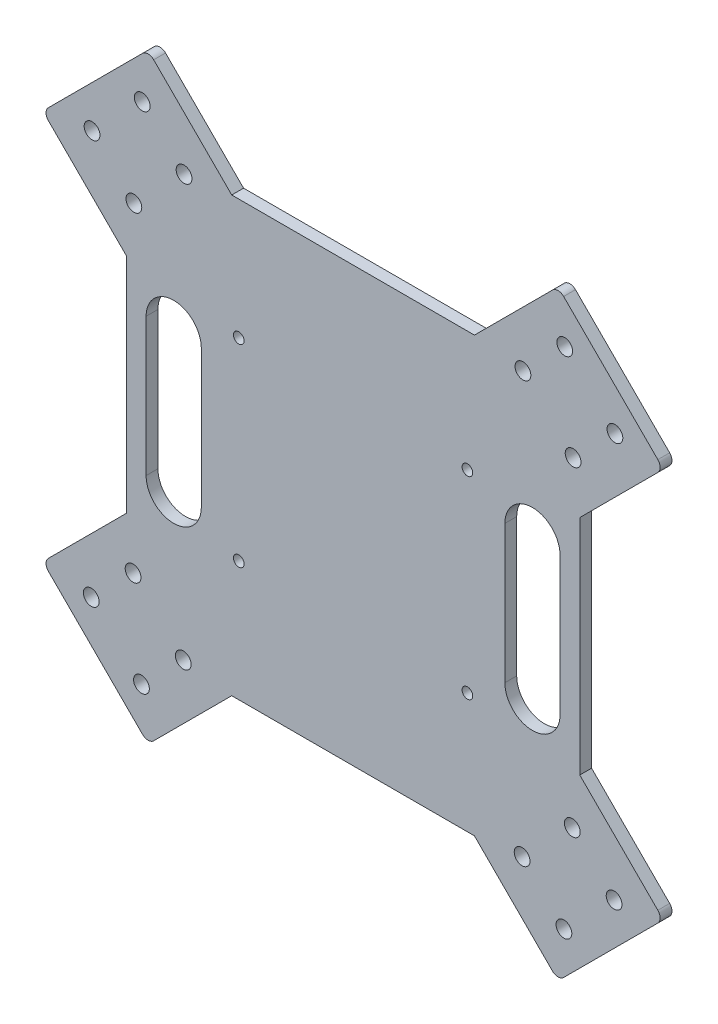
SolidWorks part; units mm, degrees
ref_plane "Front Plane" through (0, 0, 0) normal (0, 0, 1) x (1, 0, 0)
ref_plane "Top Plane" through (0, 0, 0) normal (0, 1, 0) x (1, 0, 0)
ref_plane "Right Plane" through (0, 0, 0) normal (1, 0, 0) x (0, 0, -1)
sketch "Sketch1" plane through (0, 0, 0) normal (0, 0, 1) x (1, 0, 0)
  line L0 (0, 0) -> (0, 47150.9256) construction
  line L1 (0, 0) -> (47150.9256, 0) construction
  line L7 (57.5, -28.28) -> (78.7132, -49.4932)
  line L9 (-30.78, 55) -> (30.78, 55)
  line L10 (-57.5, 28.28) -> (-57.5, -28.28)
  line L11 (-30.78, -55) -> (30.78, -55)
  line L12 (57.5, 28.28) -> (57.5, -28.28)
  line L13 (-57.5, 55) -> (57.5, -55) construction
  line L14 (-57.5, -55) -> (57.5, 55) construction
  line L18 (-29, 24.5) -> (29, 24.5) construction
  line L19 (-29, 24.5) -> (-29, -24.5) construction
  line L20 (-29, -24.5) -> (29, -24.5) construction
  line L21 (29, 24.5) -> (29, -24.5) construction
  line L22 (-29, 24.5) -> (29, -24.5) construction
  line L23 (-29, -24.5) -> (29, 24.5) construction
  line L24 (78.7132, -49.4932) -> (51.9932, -76.2132)
  line L25 (51.9932, -76.2132) -> (30.78, -55)
  line L26 (-57.5, -28.28) -> (-78.7132, -49.4932)
  line L27 (-78.7132, -49.4932) -> (-51.9932, -76.2132)
  line L28 (-51.9932, -76.2132) -> (-30.78, -55)
  line L29 (-51.9932, 76.2132) -> (-30.78, 55)
  line L30 (-78.7132, 49.4932) -> (-51.9932, 76.2132)
  line L31 (-57.5, 28.28) -> (-78.7132, 49.4932)
  line L32 (30.78, 55) -> (51.9932, 76.2132)
  line L33 (51.9932, 76.2132) -> (78.7132, 49.4932)
  line L34 (78.7132, 49.4932) -> (57.5, 28.28)
  line L35 (-28.28, -57.5) -> (-49.4932, -78.7132) [skipped]
  line L36 (-49.4932, -78.7132) -> (-76.2132, -51.9932) [skipped]
  line L37 (-76.2132, -51.9932) -> (-55, -30.78) [skipped]
  line L38 (49.4932, 78.7132) -> (76.2132, 51.9932) [skipped]
  line L39 (76.2132, 51.9932) -> (55, 30.78) [skipped]
  line L40 (28.28, 57.5) -> (49.4932, 78.7132) [skipped]
  circle A4 centre (-29, 24.5) radius 1.35
  circle A5 centre (-29, -24.5) radius 1.35
  circle A6 centre (29, 24.5) radius 1.35
  circle A7 centre (29, -24.5) radius 1.35
  arc A8 (-41.3866, 65.6066) -> (41.3866, 65.6066) centre (0, 141.0479) ccw
  arc A9 (-68.1066, 38.8866) -> (-68.1066, -38.8866) centre (-134.0876, 0) cw
  arc A10 (68.1066, 38.8866) -> (68.1066, -38.8866) centre (134.0876, 0) ccw
  arc A11 (-41.3866, -65.6066) -> (41.3866, -65.6066) centre (0, -141.0479) cw
  point P5 (0, 0)
  point P43 (0, 0)
  dimension "D3" = 58
  dimension "D4" = 2.7
  dimension "D7" = 2.7
  dimension "D8" = 2.7
  dimension "D9" = 2.7
  dimension "D1" = 49
  dimension "D5" = 115
  dimension "D6" = 110
  dimension "D10" = 45
  dimension "D11" = 30
  dimension "D12" = 45
  dimension "D14" = 45
  dimension "D15" = 45
  dimension "D16" = 30
  dimension "D17" = 45
  dimension "D18" = 45
  dimension "D19" = 30
  dimension "D20" = 37.7878
  dimension "D13" = 4
extrude "Boss-Extrude1" add sketch "Sketch1" along normal blind 3 contours L34 L33 L32 L9 L29 L30 L31 L10 L26 L27 L28 L11 L25 L24 L7 L12 A7 A6 A5 A4
sketch "Sketch2" plane through (0, 0, 3) normal (0, 0, 1) x (1, 0, 0)
  line L0 (30.78, 55) -> (57.5, 28.28) construction
  line L1 (44.14, 41.64) -> (71.2882, 68.7882) construction
  line L2 (43.0793, 53.3073) -> (53.6859, 63.9139) construction
  line L3 (43.0793, 53.3073) -> (55.8073, 40.5793) construction
  line L4 (55.8073, 40.5793) -> (66.4139, 51.1859) construction
  line L5 (53.6859, 63.9139) -> (66.4139, 51.1859) construction
  line L6 (43.0793, 53.3073) -> (66.4139, 51.1859) construction
  line L7 (55.8073, 40.5793) -> (53.6859, 63.9139) construction
  line L8 (0, 0) -> (-36037.9104, 34659.328) construction
  line L9 (-57.5, -28.28) -> (-30.78, -55) construction
  line L10 (-78.7132, -49.4932) -> (-51.9932, -76.2132) construction
  line L11 (-65.3532, -62.8532) -> (-37.2147, -34.7147) construction
  line L12 (-78.7132, 49.4932) -> (-51.9932, 76.2132) construction
  line L13 (-57.5, 28.28) -> (-30.78, 55) construction
  line L14 (-66.4139, -51.1859) -> (-55.8073, -40.5793) construction
  line L15 (-66.4139, -51.1859) -> (-53.6859, -63.9139) construction
  line L16 (-53.6859, -63.9139) -> (-43.0793, -53.3073) construction
  line L17 (-55.8073, -40.5793) -> (-43.0793, -53.3073) construction
  line L18 (-66.4139, -51.1859) -> (-43.0793, -53.3073) construction
  line L19 (-53.6859, -63.9139) -> (-55.8073, -40.5793) construction
  line L20 (30.78, -55) -> (57.5, -28.28) construction
  line L21 (-41.3866, 65.6066) -> (-68.1066, 38.8866) construction
  line L22 (-66.207, 51.3928) -> (-53.4791, 64.1207) construction
  line L23 (-66.207, 51.3928) -> (-55.6004, 40.7862) construction
  line L24 (-55.6004, 40.7862) -> (-42.8725, 53.5141) construction
  line L25 (-53.4791, 64.1207) -> (-42.8725, 53.5141) construction
  line L26 (-66.207, 51.3928) -> (-42.8725, 53.5141) construction
  line L27 (-55.6004, 40.7862) -> (-53.4791, 64.1207) construction
  line L28 (-51.9932, 76.2132) -> (-30.78, 55) construction
  line L29 (-57.5, 28.28) -> (-78.7132, 49.4932) construction
  line L31 (42.8725, -53.5141) -> (55.6004, -40.7862) construction
  line L32 (42.8725, -53.5141) -> (53.4791, -64.1207) construction
  line L33 (53.4791, -64.1207) -> (66.207, -51.3928) construction
  line L34 (55.6004, -40.7862) -> (66.207, -51.3928) construction
  line L35 (42.8725, -53.5141) -> (66.207, -51.3928) construction
  line L36 (53.4791, -64.1207) -> (55.6004, -40.7862) construction
  line L55 (-45.5, 17.5) -> (-45.5, -17.5) construction
  line L56 (-38.5, 17.5) -> (-38.5, -17.5)
  line L57 (-52.5, 17.5) -> (-52.5, -17.5)
  line L58 (-57.5, 0) -> (-26.4925, 0) construction
  line L59 (-57.5, 28.28) -> (-57.5, -28.28) construction
  line L60 (0, 0) -> (0, 50000) construction
  line L61 (45.5, 17.5) -> (45.5, -17.5) construction
  line L62 (38.5, 17.5) -> (38.5, -17.5)
  line L63 (52.5, 17.5) -> (52.5, -17.5)
  circle A0 centre (43.0793, 53.3073) radius 2
  circle A1 centre (53.6859, 63.9139) radius 2
  circle A2 centre (55.8073, 40.5793) radius 2
  circle A3 centre (66.4139, 51.1859) radius 2
  circle A4 centre (-66.4139, -51.1859) radius 2
  circle A5 centre (-55.8073, -40.5793) radius 2
  circle A6 centre (-43.0793, -53.3073) radius 2
  circle A7 centre (-53.6859, -63.9139) radius 2
  circle A8 centre (-53.4791, 64.1207) radius 2
  circle A9 centre (-42.8725, 53.5141) radius 2
  circle A10 centre (-55.6004, 40.7862) radius 2
  circle A11 centre (-66.207, 51.3928) radius 2
  circle A12 centre (55.6004, -40.7862) radius 2
  circle A13 centre (42.8725, -53.5141) radius 2
  circle A14 centre (66.207, -51.3928) radius 2
  circle A15 centre (53.4791, -64.1207) radius 2
  arc A36 (-38.5, 17.5) -> (-52.5, 17.5) centre (-45.5, 17.5) ccw
  arc A37 (-52.5, -17.5) -> (-38.5, -17.5) centre (-45.5, -17.5) ccw
  arc A38 (38.5, 17.5) -> (52.5, 17.5) centre (45.5, 17.5) cw
  arc A39 (52.5, -17.5) -> (38.5, -17.5) centre (45.5, -17.5) cw
  point P4 (54.7466, 52.2466)
  point P18 (-54.7466, -52.2466)
  point P32 (-44.14, -41.64)
  point P38 (-65.3532, 62.8532)
  point P47 (-54.5398, 52.4534)
  point P53 (-52.6697, 53.5593)
  point P63 (54.5398, -52.4534)
  point P79 (0, 16.7172)
  point P82 (19.1707, 46)
  point P85 (-19.1707, 46)
  point P92 (-45.5, 0)
  point P114 (45.5, 0)
  point P120 (0, 0)
  dimension "D8" = 4
  dimension "D9" = 4
  dimension "D10" = 4
  dimension "D11" = 4
  dimension "D12" = 18
  dimension "D19" = 4
  dimension "D20" = 4
  dimension "D21" = 4
  dimension "D22" = 4
  dimension "D29" = 4
  dimension "D30" = 4
  dimension "D31" = 4
  dimension "D32" = 4
  dimension "D40" = 4
  dimension "D41" = 4
  dimension "D42" = 4
  dimension "D43" = 4
  dimension "D53" = 7
  dimension "D1" = 15
  dimension "D2" = 18
  dimension "D3" = 90
  dimension "D4" = 90
  dimension "D5" = 90
  dimension "D6" = 15
  dimension "D7" = 90
  dimension "D13" = 90
  dimension "D14" = 90
  dimension "D15" = 90
  dimension "D16" = 15
  dimension "D17" = 90
  dimension "D18" = 15
  dimension "D23" = 90
  dimension "D24" = 90
  dimension "D25" = 90
  dimension "D26" = 90
  dimension "D27" = 15
  dimension "D28" = 18
  dimension "D33" = 90
  dimension "D34" = 90
  dimension "D35" = 90
  dimension "D36" = 90
  dimension "D37" = 15
  dimension "D38" = 18
  dimension "D39" = 15
  dimension "D45" = 35
  dimension "D46" = 35
  dimension "D52" = 12
  dimension "D54" = 31.0075
  dimension "D55" = 35
extrude "Cut-Extrude1" cut sketch "Sketch2" against normal through all
fillet "Fillet1" radius 2 8 edges at (-51.9932, 76.2132, 1.5) (-78.7132, 49.4932, 1.5) (51.9932, 76.2132, 1.5) (78.7132, 49.4932, 1.5) (78.7132, -49.4932, 1.5) (51.9932, -76.2132, 1.5) (-78.7132, -49.4932, 1.5) (-51.9932, -76.2132, 1.5)
sketch3d "3DSketch3"
  line L0 (0, 45, 0) -> (0, 20, 25)
  line L1 (0, 20, 25) -> (0, -20, 25)
  line L2 (0, -20, 25) -> (0, -45, 0)
  line L3 (0, 0, 0) -> (0, 0, 50000) construction
  line L4 (0, 0, 0) -> (0, 50000, 0) construction
  line L5 (0, -47.8284, 0) -> (0, -20.8284, 27)
  line L6 (-44, -28, 0) -> (44, -28, 0) construction
  line L7 (-44, -28, 0) -> (-44, 28, 0) construction
  line L8 (-44, 28, 0) -> (44, 28, 0) construction
  line L9 (44, -28, 0) -> (44, 28, 0) construction
  line L10 (-44, -28, 0) -> (44, 28, 0) construction
  line L11 (-44, 28, 0) -> (44, -28, 0) construction
  line L12 (0, -20.8284, 27) -> (0, 20.83, 27)
  line L13 (0, 20.83, 27) -> (0, 47.83, 0)
  point P4 (0, 0, 0)
  point P6 (0, 0, 0)
  point P7 (0, 0, 0)
  point P8 (0, 0, 0)
  point P13 (0, 0, 0)
  dimension "D1" = 2
  dimension "D10" = 2.83
  dimension "D2" = 2
  dimension "D3" = 45
  dimension "D4" = 45
  dimension "D5" = 45
  dimension "D6" = 45
  dimension "D7" = 25
  dimension "D8" = 56
  dimension "D9" = 88
